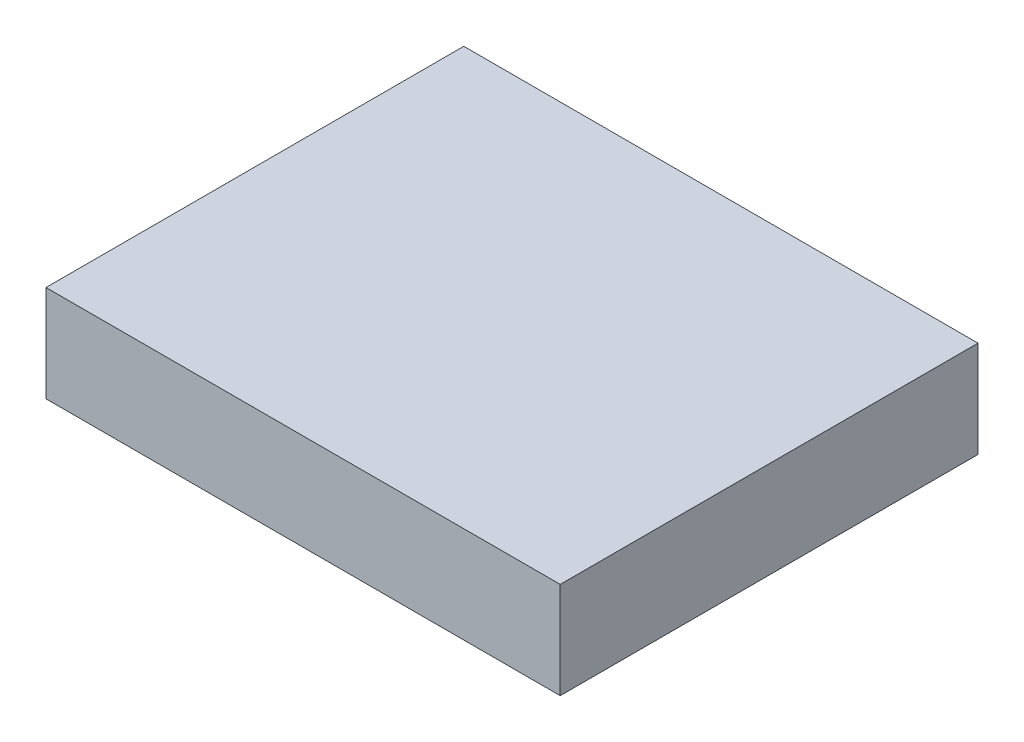
SolidWorks part; units mm, degrees
ref_plane "前视基准面" through (0, 0, 0) normal (0, 0, 1) x (1, 0, 0)
ref_plane "上视基准面" through (0, 0, 0) normal (0, 1, 0) x (1, 0, 0)
ref_plane "右视基准面" through (0, 0, 0) normal (1, 0, 0) x (0, 0, -1)
sketch "草图1" plane through (0, 0, 0) normal (0, 1, 0) x (1, 0, 0)
  line L1 (-80, 65) -> (80, 65)
  line L2 (-80, 65) -> (-80, -65)
  line L3 (-80, -65) -> (80, -65)
  line L4 (80, 65) -> (80, -65)
  dimension "D1" = 160
  dimension "D2" = 130
  dimension "D3" = 65
  dimension "D4" = 80
extrude "凸台-拉伸1" add sketch "草图1" along normal blind 30
